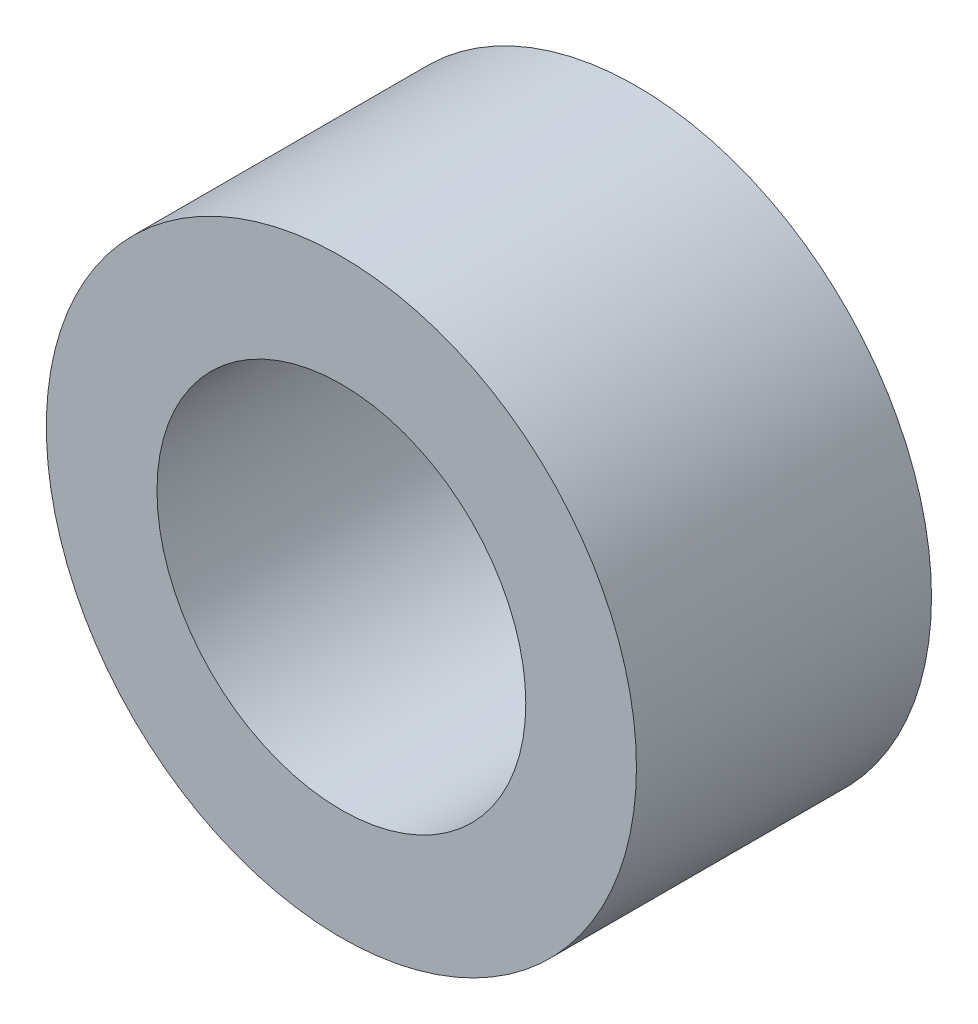
SolidWorks part; units mm, degrees
ref_plane "Ön Düzlem" through (0, 0, 0) normal (0, 0, 1) x (1, 0, 0)
ref_plane "Üst Düzlem" through (0, 0, 0) normal (0, 1, 0) x (1, 0, 0)
ref_plane "Sağ Düzlem" through (0, 0, 0) normal (1, 0, 0) x (0, 0, -1)
sketch "Çizim1" plane through (0, 0, 0) normal (0, 0, 1) x (1, 0, 0)
  circle A0 centre (0, 0) radius 5
  circle A1 centre (0, 0) radius 3.125
  dimension "D1" = 6.25
  dimension "D2" = 10
extrude "Yükseklik-Ekstrüzyon1" add sketch "Çizim1" along normal blind 5
